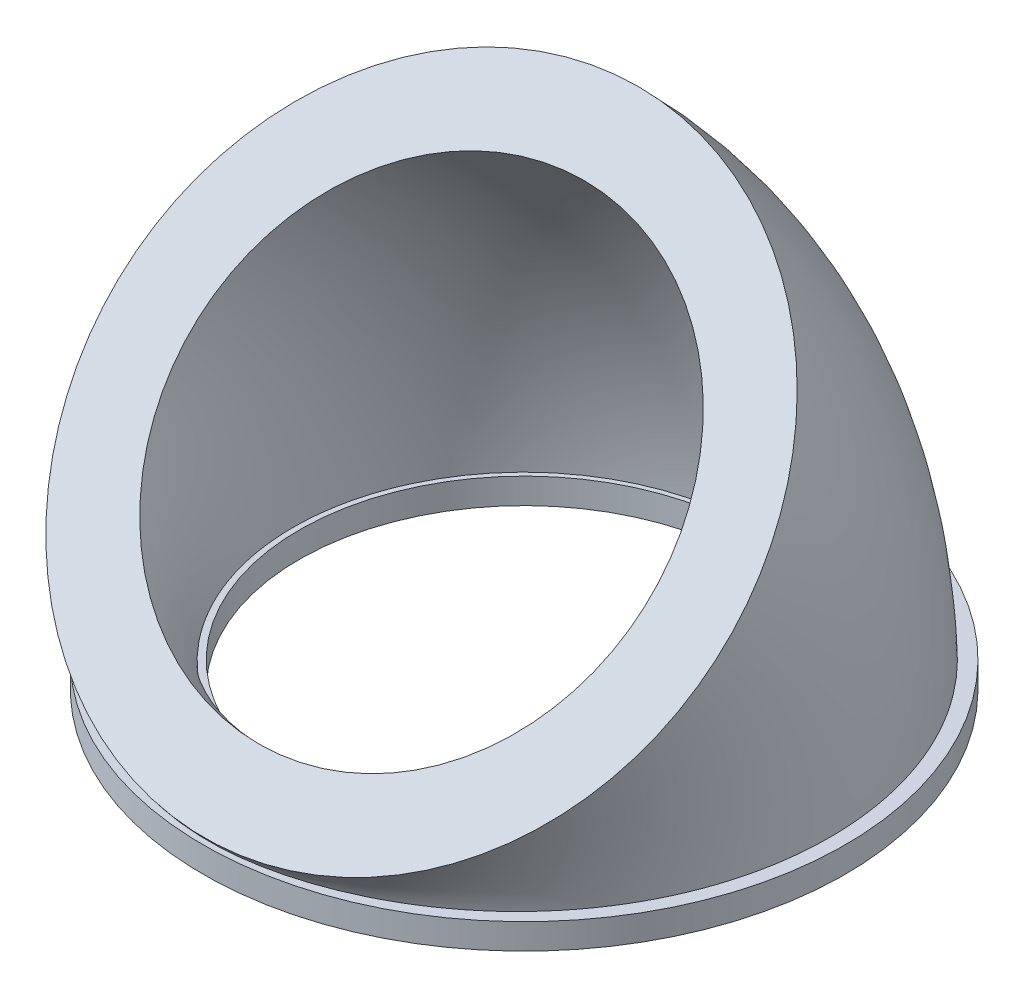
SolidWorks part; units mm, degrees
ref_plane "Спереди" through (0, 0, 0) normal (0, 0, 1) x (1, 0, 0)
ref_plane "Сверху" through (0, 0, 0) normal (0, 1, 0) x (1, 0, 0)
ref_plane "Справа" through (0, 0, 0) normal (1, 0, 0) x (0, 0, -1)
sketch "Sketch1" plane through (0, 0, 0) normal (0, 0, 1) x (1, 0, 0)
  circle A61 centre (0, 0) radius 24
  circle A464 centre (0, 0) radius 18
  dimension "D1" = 36
  dimension "D2" = 48
sketch "Sketch2" plane through (0, 0, 0) normal (1, 0, 0) x (0, 0, -1)
  line L0 (0, 0) -> (10, 0)
  line L1 (37.4234, -27.4234) -> (37.4234, -34.4234)
  arc A0 (10, 0) -> (37.4234, -27.4234) centre (10, -27.4234) cw
  dimension "D1" = 27.4234
sweep "Sweep1" add profiles "Sketch1" path "Sketch2"
sketch "Sketch3" plane through (0, 0, 0) normal (1, 0, 0) x (0, 0, -1)
  line L0 (12.4207, -25.0027) -> (49.6108, 12.1875) construction
  line L1 (49.6108, 12.1875) -> (82.7565, -20.9582)
  line L2 (82.7565, -20.9582) -> (61.4234, -27.4234)
  line L3 (61.4234, -27.4234) -> (10, -27.4234)
  line L4 (10, -27.4234) -> (49.6108, 12.1875)
  line L5 (49.6108, 12.1875) -> (-2.9582, 64.7564)
  line L6 (-2.9582, 64.7564) -> (-4.559, -41.9824)
  line L7 (-4.559, -41.9824) -> (10, -27.4234)
  line L8 (82.7565, -20.9582) -> (82.7565, -43.292)
  line L9 (82.7565, -43.292) -> (-4.559, -41.9824)
  arc A0 (13.4234, -27.4234) -> (10, -24) centre (10, -27.4234) ccw construction
extrude "Cut-Extrude1" cut sketch "Sketch3" against normal through all both and the other way through all contours L6 L7 L4 L5 | L9 L8 L2 L3 L7
sketch "Sketch4" plane through (0, -27.4234, 0) normal (0, -1, 0) x (-1, 0, 0)
  circle A0 centre (0, 37.4234) radius 17.5893
  circle A1 centre (0, 37.4234) radius 25.1087
extrude "Boss-Extrude2" add sketch "Sketch4" against normal blind 2
sketch "Sketch5" [suppressed] plane through (0, -18.7117, -18.7117) normal (0, 0.7071, 0.7071) x (1, 0, 0)
  circle A0 centre (0, 15.1032) radius 17.6775
  circle A1 centre (0, 15.1032) radius 22.5322
sketch "Sketch6" plane through (0, 0, 0) normal (0, 0, 1) x (1, 0, 0)
  circle A0 centre (0, 0) radius 20.5
  circle A1 centre (2.3821, 0) radius 24
